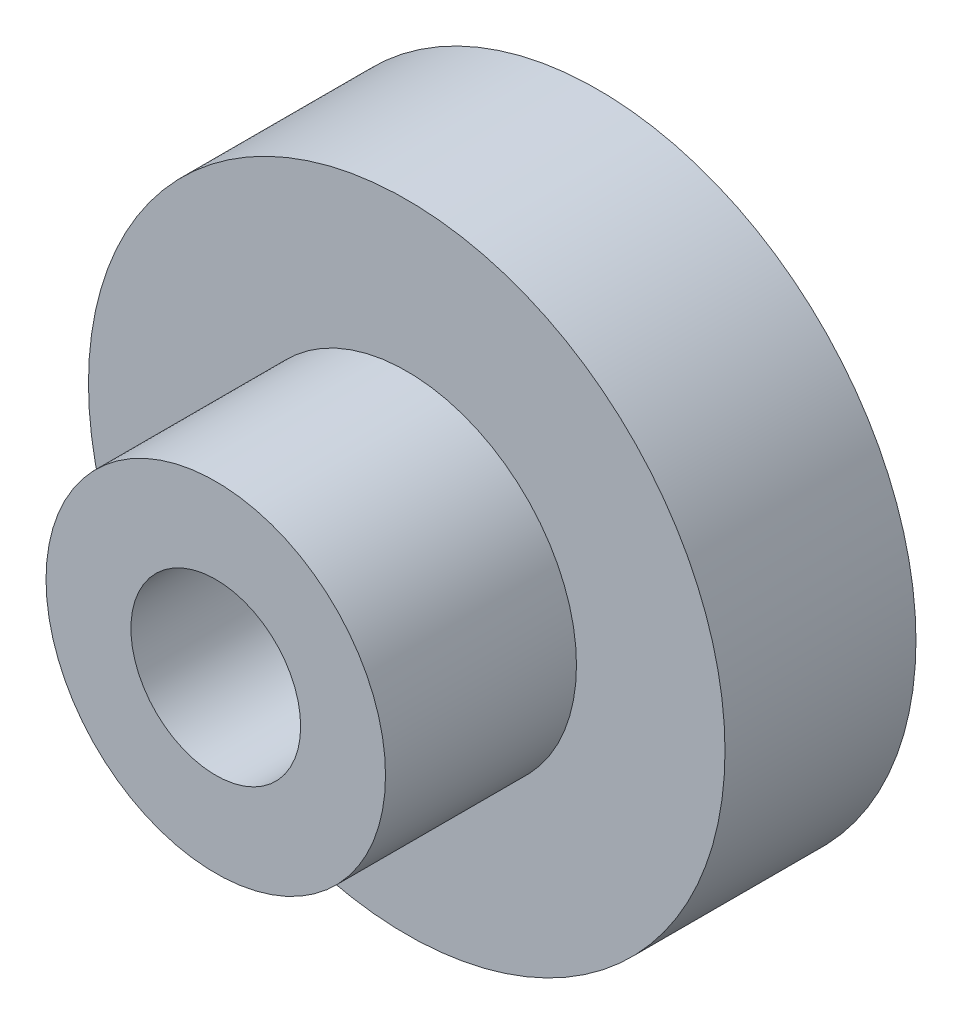
SolidWorks part; units mm, degrees
ref_plane "前视基准面" through (0, 0, 0) normal (0, 0, 1) x (1, 0, 0)
ref_plane "上视基准面" through (0, 0, 0) normal (0, 1, 0) x (1, 0, 0)
ref_plane "右视基准面" through (0, 0, 0) normal (1, 0, 0) x (0, 0, -1)
sketch "草图1" plane through (0, 0, 0) normal (0, 0, 1) x (1, 0, 0)
  circle A0 centre (0, 0) radius 15
  dimension "D1" = 30
extrude "凸台-拉伸1" add sketch "草图1" along normal blind 9
sketch "草图2" plane through (0, 0, 9) normal (0, 0, 1) x (1, 0, 0)
  circle A0 centre (0, 0) radius 8
  dimension "D1" = 16
extrude "凸台-拉伸2" add sketch "草图2" along normal blind 9
sketch "草图3" plane through (0, 0, 18) normal (0, 0, 1) x (1, 0, 0)
  circle A0 centre (0, 0) radius 4
  dimension "D1" = 8
extrude "切除-拉伸1" cut sketch "草图3" against normal blind 28
sketch "草图4" plane through (0, 0, 0) normal (0, 1, 0) x (1, 0, 0)
  circle A0 centre (0, -4) radius 3
  dimension "D2" = 6
extrude "切除-拉伸2" cut sketch "草图4" against normal blind 28
